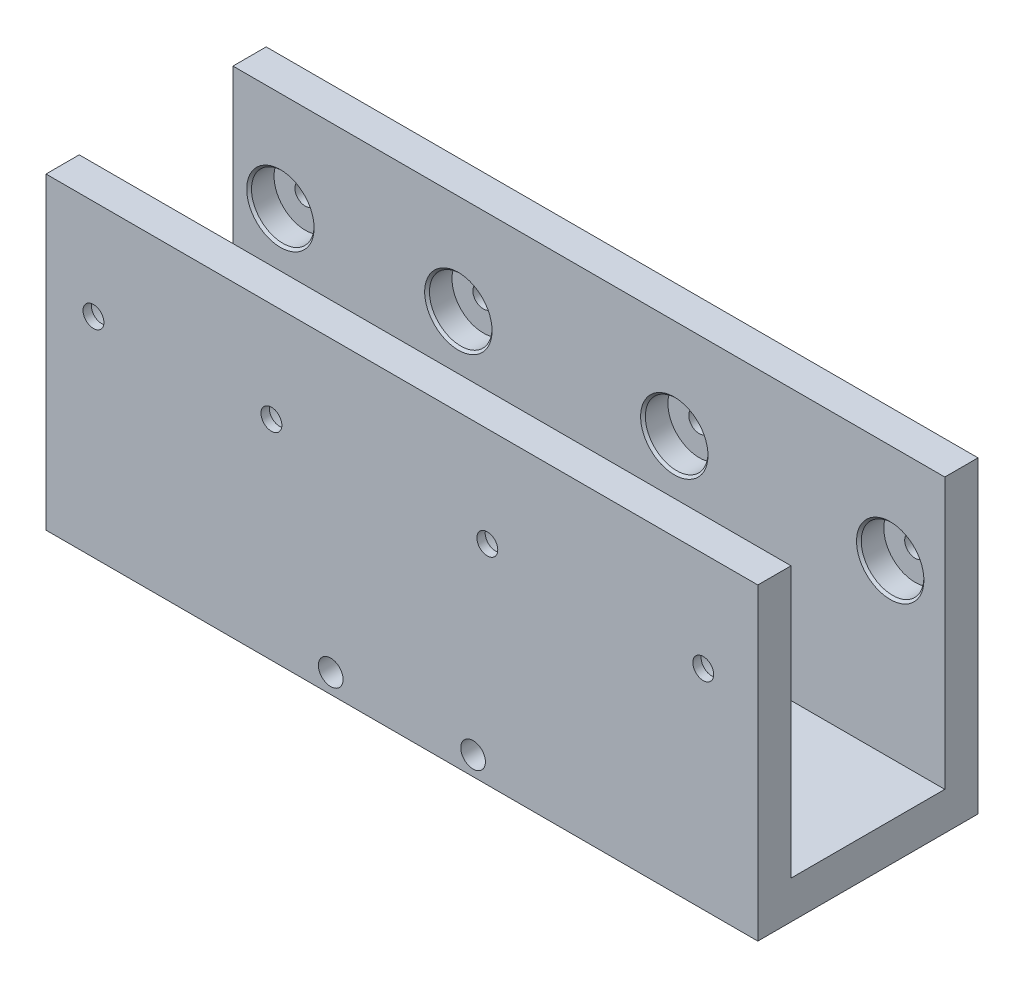
SolidWorks part; units mm, degrees
ref_plane "Front Plane" through (0, 0, 0) normal (0, 0, 1) x (1, 0, 0)
ref_plane "Top Plane" through (0, 0, 0) normal (0, 1, 0) x (1, 0, 0)
ref_plane "Right Plane" through (0, 0, 0) normal (1, 0, 0) x (0, 0, -1)
sketch "Sketch1" plane through (0, 0, 0) normal (0, 0, 1) x (1, 0, 0)
  line L1 (0, 0) -> (150, 0)
  line L2 (0, 0) -> (0, 65)
  line L3 (0, 65) -> (150, 65)
  line L4 (150, 0) -> (150, 65)
  dimension "D1" = 150
  dimension "D2" = 65
extrude "Boss-Extrude1" add sketch "Sketch1" along normal blind 7
sketch "Sketch2" plane through (0, 0, 7) normal (0, 0, 1) x (1, 0, 0)
  line L0 (0, 0) -> (150, 0) construction
  line L1 (0, 65) -> (0, 0) construction
  circle A0 centre (10, 44) radius 2.2
  circle A1 centre (47.5, 44) radius 2.2
  circle A2 centre (93, 44) radius 2.2
  circle A3 centre (138.5, 44) radius 2.2
  point P8 (0, 0)
  point P9 (-0.5162, 33.4546)
  point P10 (137.3785, 29.6275)
  dimension "D1" = 4.4
  dimension "D2" = 37.5
  dimension "D3" = 45.5
  dimension "D4" = 45.5
  dimension "D5" = 44
  dimension "D6" = 10
extrude "Cut-Extrude1" cut sketch "Sketch2" against normal up to next
sketch "Sketch3" plane through (0, 0, 0) normal (0, 0, -1) x (-1, 0, 0)
  line L0 (0, 65) -> (0, 0) construction
  line L1 (-150, 0) -> (0, 0)
  line L2 (-150, 0) -> (-150, 8)
  line L3 (-150, 8) -> (0, 8)
  line L4 (0, 0) -> (0, 8)
  dimension "D1" = 8
extrude "Boss-Extrude2" add sketch "Sketch3" along normal blind 16.2
sketch "Sketch4" plane through (0, 0, 0) normal (0, 0, -1) x (-1, 0, 0)
  circle A0 centre (-138.5, 44) radius 6.6
  circle A1 centre (-93, 44) radius 6.6
  circle A2 centre (-47.5, 44) radius 6.6
  circle A3 centre (-10, 44) radius 6.6
  dimension "D1" = 13.2
extrude "Cut-Extrude2" cut sketch "Sketch4" against normal blind 5.25
mirror "Mirror2" about plane through (0, 0, -16.2) normal (0, 0, 1) of "Boss-Extrude2"
ref_plane "Plane2" through (0, 0, -16.2) normal (0, 0, -1) x (-1, 0, 0)
mirror "Mirror3" about plane through (0, 0, -16.2) normal (0, 0, -1) of "Cut-Extrude2", "Cut-Extrude1", "Boss-Extrude1"
chamfer "Chamfer1" distance 0.5 angle 45 8 edges at (3.4, 44, -32.4) (40.9, 44, -32.4) (86.4, 44, -32.4) (131.9, 44, -32.4) (3.4, 44, 0) (40.9, 44, 0) (86.4, 44, 0) (131.9, 44, 0)
sketch "Sketch5" plane through (0, 0, 7) normal (0, 0, 1) x (1, 0, 0)
  line L0 (60, 4.0521) -> (90, 4) construction
  line L1 (0, 0) -> (150, 0) construction
  circle A0 centre (60, 4.0521) radius 2.6
  circle A1 centre (90, 4) radius 2.6
  point P6 (75, 0)
  point P7 (75, 4.0261)
  dimension "D1" = 5.2
  dimension "D2" = 30
  dimension "D3" = 4
extrude "Cut-Extrude3" cut sketch "Sketch5" against normal blind 7
sketch "Sketch7" plane through (0, 0, 0) normal (0, 0, 1) x (1, 0, 0)
  circle A0 centre (60, 4.0521) radius 1.5
  circle A1 centre (90, 4) radius 1.5
  dimension "D1" = 3
extrude "Cut-Extrude4" cut sketch "Sketch7" against normal through all
